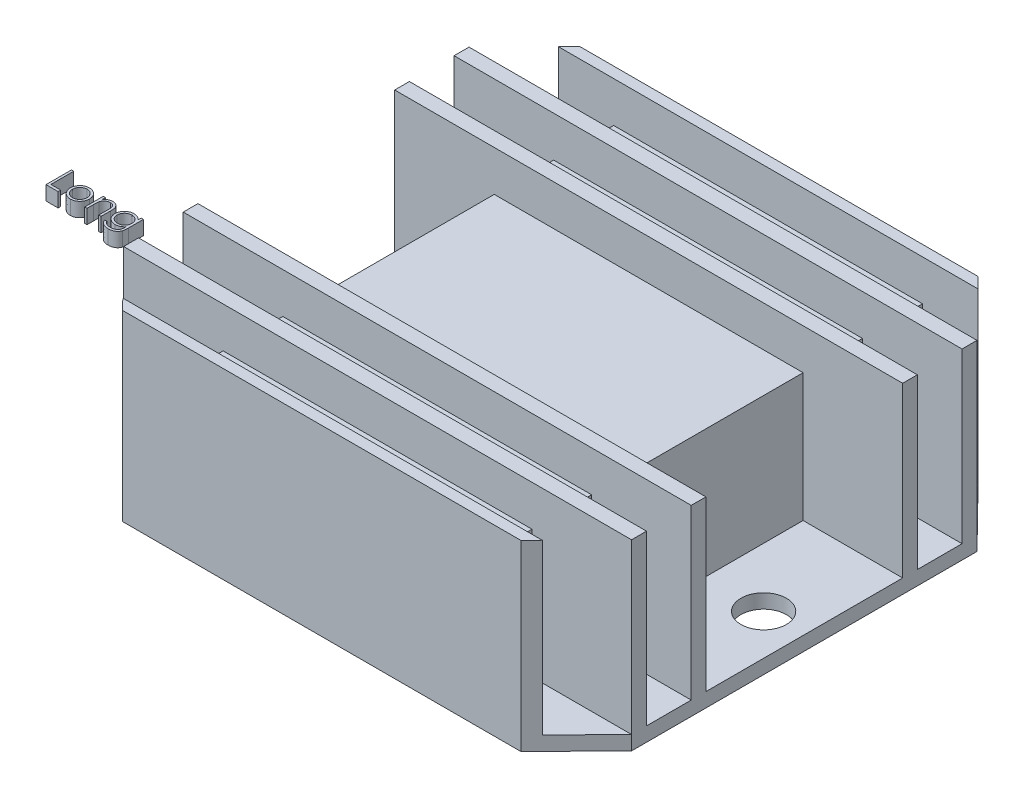
SolidWorks part; units mm, degrees
ref_plane "Front Plane" through (0, 0, 0) normal (0, 0, 1) x (1, 0, 0)
ref_plane "Top Plane" through (0, 0, 0) normal (0, 1, 0) x (1, 0, 0)
ref_plane "Right Plane" through (0, 0, 0) normal (1, 0, 0) x (0, 0, -1)
sketch "Sketch1" plane through (0, 0, 0) normal (0, 1, 0) x (1, 0, 0)
  line L0 (0, 49.1649) -> (0, -58.9901) construction
  line L1 (-24.892, -28.575) -> (24.892, -28.575)
  line L2 (-31.75, -21.59) -> (-31.75, 21.59)
  line L3 (-24.892, 28.575) -> (24.892, 28.575)
  line L4 (31.75, -21.59) -> (31.75, 21.59)
  line L5 (-28.1092, -25.2983) -> (28.1092, 25.2983) construction
  line L6 (-28.1092, 25.2983) -> (28.1092, -25.2983) construction
  line L7 (-58.1045, 0) -> (71.2438, 0) construction
  line L8 (-31.75, 21.59) -> (-24.892, 28.575)
  line L9 (24.892, 28.575) -> (31.75, 21.59)
  line L10 (31.75, -21.59) -> (24.892, -28.575)
  line L11 (-31.75, -21.59) -> (-24.892, -28.575)
  text T0 "Long"
  point P0 (0, 0)
  point P6 (-31.75, 21.59)
  point P7 (-24.892, 28.575)
  point P12 (-31.75, -21.59)
  point P13 (-24.892, -28.575)
  point P14 (24.892, -28.575)
  point P15 (31.75, -21.59)
  point P16 (31.75, 21.59)
  point P17 (24.892, 28.575)
extrude "Boss-Extrude1" add sketch "Sketch1" along normal blind 1.778
sketch "Sketch2" plane through (0, 1.778, 0) normal (0, 1, 0) x (1, 0, 0)
  line L0 (-24.892, 28.575) -> (-26.2193, 27.2231)
  line L1 (-24.892, 28.575) -> (-31.75, 21.59) construction
  line L2 (-26.2193, 27.2231) -> (26.2193, 27.2231)
  line L3 (31.75, 21.59) -> (24.892, 28.575) construction
  line L4 (26.2193, 27.2231) -> (24.892, 28.575)
  line L5 (24.892, 28.575) -> (-24.892, 28.575)
  line L6 (-48.6675, 0) -> (46.6359, 0) construction
  line L7 (26.2193, -27.2231) -> (24.892, -28.575)
  line L8 (24.892, -28.575) -> (-24.892, -28.575)
  line L9 (-26.2193, -27.2231) -> (26.2193, -27.2231)
  line L10 (-24.892, -28.575) -> (-26.2193, -27.2231)
  line L11 (-31.75, 21.59) -> (31.75, 21.59)
  line L12 (31.75, 21.59) -> (31.75, 19.7227)
  line L13 (31.75, -21.59) -> (31.75, 21.59) construction
  line L14 (31.75, 19.7227) -> (-31.75, 19.7227)
  line L15 (-31.75, 21.59) -> (-31.75, -21.59) construction
  line L16 (-31.75, 19.7227) -> (-31.75, 21.59)
  line L17 (31.75, -21.59) -> (31.75, -19.7227)
  line L18 (-31.75, -21.59) -> (31.75, -21.59)
  line L19 (-31.75, -19.7227) -> (-31.75, -21.59)
  line L20 (31.75, -19.7227) -> (-31.75, -19.7227)
  line L21 (-31.75, 14.1347) -> (-31.75, 12.2991)
  line L22 (-31.75, 12.2991) -> (31.75, 12.2991)
  line L23 (31.75, 12.2991) -> (31.75, 14.1347)
  line L24 (31.75, 14.1347) -> (-31.75, 14.1347)
  line L25 (31.75, -12.2991) -> (31.75, -14.1347)
  line L26 (31.75, -14.1347) -> (-31.75, -14.1347)
  line L27 (-31.75, -14.1347) -> (-31.75, -12.2991)
  line L28 (-31.75, -12.2991) -> (31.75, -12.2991)
  point P31 (-31.75, 14.1347)
  dimension "D1" = 1.3519
extrude "Boss-Extrude2" add sketch "Sketch2" along normal blind 21.082
sketch "Sketch3" plane through (0, 0, 0) normal (0, 1, 0) x (1, 0, 0)
  line L0 (-24.892, -28.575) -> (24.892, -28.575) construction
  line L1 (-19.304, 28.575) -> (19.304, 28.575)
  line L2 (-19.304, 28.575) -> (-19.304, -28.575)
  line L3 (-19.304, -28.575) -> (19.304, -28.575)
  line L4 (19.304, 28.575) -> (19.304, -28.575)
  line L5 (-19.304, 28.575) -> (19.304, -28.575) construction
  line L6 (-19.304, -28.575) -> (19.304, 28.575) construction
  point P0 (0, 0)
extrude "Boss-Extrude3" add sketch "Sketch3" along normal blind 17.78
sketch "Sketch4" plane through (0, 0, 0) normal (0, -1, 0) x (1, 0, 0)
  line L0 (-46.1417, 0) -> (40.7098, 0) construction
  line L1 (0, 33.5651) -> (0, -34.7309) construction
  circle A0 centre (-26.67, 0) radius 2.8428
  circle A1 centre (26.67, 0) radius 2.8428
extrude "Cut-Extrude1" cut sketch "Sketch4" against normal through all
